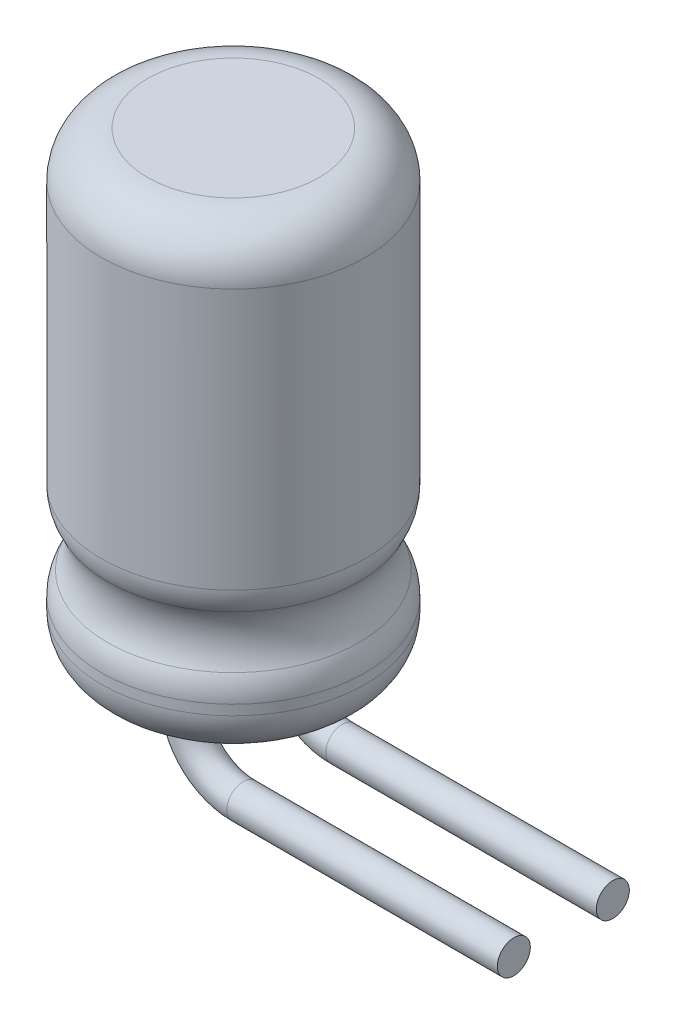
SolidWorks part; units mm, degrees
ref_plane "Спереди" through (0, 0, 0) normal (0, 0, 1) x (1, 0, 0)
ref_plane "Сверху" through (0, 0, 0) normal (0, 1, 0) x (1, 0, 0)
ref_plane "Справа" through (0, 0, 0) normal (1, 0, 0) x (0, 0, -1)
sketch "Эскиз1" plane through (0, 0, 0) normal (0, 1, 0) x (1, 0, 0)
  circle A0 centre (0, 0) radius 2
extrude "Бобышка-Вытянуть1" add sketch "Эскиз1" along normal blind 7 contours A0
sketch "Эскиз2" plane through (0, 0, 0) normal (0, -1, 0) x (1, 0, 0)
  line L0 (0, 0) -> (0, 0.75) construction
  circle A0 centre (0, 0.75) radius 0.25
sketch3d "Трехмерный эскиз1"
  line L0 (0, 0, 0.75) -> (0, -0.1, 0.75)
  line L1 (0.9, -1, 0.75) -> (5, -1, 0.75)
  arc A0 (0, -0.1, 0.75) -> (0.9, -1, 0.75) centre (0.9, -0.1, 0.75) ccw
  point P6 (0, -1, 0.75)
  point P7 (0.9, -0.1, 1.65)
  dimension "D1" = 0.9
sweep "По траектории1" add profiles "Эскиз2" path "Трехмерный эскиз1"
ref_axis "Ось1" through (0, 0, 0) along (0, -1, 0)
ref_plane "Плоскость1" through (0, 0, 0) normal (1, 0, 0) x (0, 0, -1)
ref_plane "Плоскость2" through (0, 0, 0) normal (0, 0, 1) x (0, -1, 0)
mirror "Зеркальное отражение1" about plane through (0, 0, 0) normal (0, 0, 1) of "По траектории1"
fillet "Скругление1" radius 0.7 1 edges at (0, 0, 2)
fillet "Скругление2" radius 0.7 1 edges at (0, 7, 2)
sketch "Эскиз3" plane through (0, 0, 0) normal (1, 0, 0) x (0, 0, -1)
  line L0 (0, 0) -> (-2.6, 0) construction
  line L1 (-2.6, 0) -> (-2.6, 1.6) construction
  circle A0 centre (-2.6, 1.6) radius 0.8
revolve "Вырез-Повернуть1" cut sketch "Эскиз3" angle 360 about axis through (0, 0, 0) along (0, -1, 0)
fillet "Скругление3" radius 0.7 1 edges at (0, 1.0708, 2)
fillet "Скругление4" radius 0.7 1 edges at (0, 2.1292, -2)
